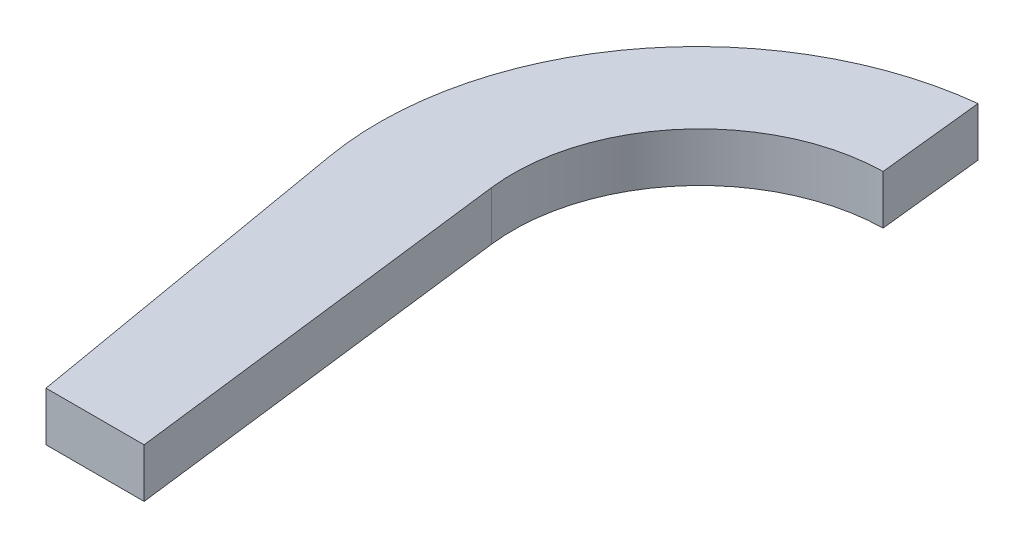
SolidWorks part; units mm, degrees
material "Pine"
ref_plane "Front Plane" through (0, 0, 0) normal (0, 0, 1) x (1, 0, 0)
ref_plane "Top Plane" through (0, 0, 0) normal (0, 1, 0) x (1, 0, 0)
ref_plane "Right Plane" through (0, 0, 0) normal (1, 0, 0) x (0, 0, -1)
sketch "Sketch1" plane through (0, 0, 0) normal (0, 1, 0) x (1, 0, 0)
  line L60 (-19.05, 0) -> (19.05, 0)
  line L61 (70.5967, 235.4044) -> (66.191, 276.6594)
  line L62 (19.05, 0) -> (0, 153.9468)
  line L63 (-19.05, 0) -> (-41.9502, 132.9979)
  arc A15 (0, 153.9468) -> (70.5967, 235.4044) centre (72.0112, 162.8577) cw
  arc A16 (-41.9502, 132.9979) -> (66.191, 276.6594) centre (79.7151, 153.9468) cw
  point P2 (0, 0)
  point P8 (-34.9352, 107.747)
  point P10 (-19.05, 104.1636)
  point P11 (34.9249, 93.9316)
  point P12 (108.3905, 190.9124)
  point P13 (91.6919, 165.3735)
  point P14 (23.5879, 107.747)
  point P15 (23.5879, 0)
  point P16 (23.5879, 0)
  point P17 (66.191, 276.6594)
  point P18 (-44.9982, 132.9979)
  point P19 (70.5967, 235.4044)
  point P20 (6.4288, 158.0028)
  point P21 (0, 153.9468)
  dimension "D1" = 38.1
extrude "Boss-Extrude1" add sketch "Sketch1" along normal blind 19.05
